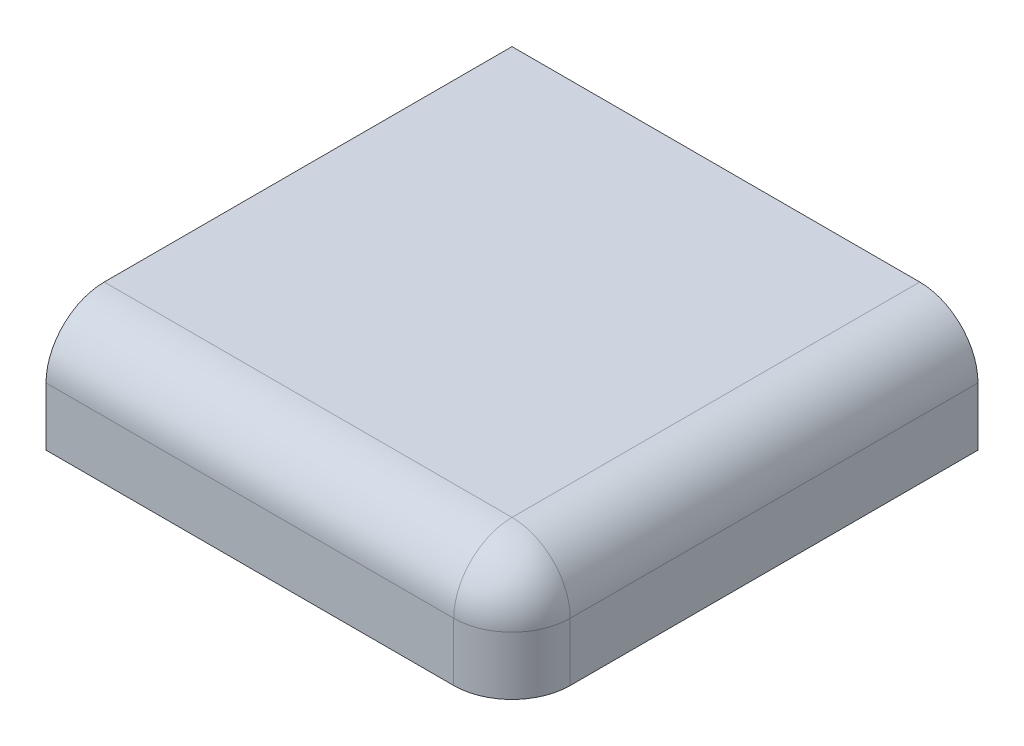
SolidWorks part; units mm, degrees
ref_plane "Front Plane" through (0, 0, 0) normal (0, 0, 1) x (1, 0, 0)
ref_plane "Top Plane" through (0, 0, 0) normal (0, 1, 0) x (1, 0, 0)
ref_plane "Right Plane" through (0, 0, 0) normal (1, 0, 0) x (0, 0, -1)
sketch "Эскиз1" plane through (0, 0, 0) normal (0, 1, 0) x (1, 0, 0)
  line L0 (-20, -20) -> (20, -20)
  line L1 (-20, -20) -> (-20, 20)
  line L2 (20, -20) -> (20, 20)
  line L3 (-20, 20) -> (20, 20)
  line L4 (-20, -20) -> (20, 20) construction
  line L5 (20, -20) -> (-20, 20) construction
  point P1 (0, 0)
  dimension "D1" = 40
  dimension "D2" = 40
extrude "Бобышка-Вытянуть1" add sketch "Эскиз1" against normal blind 10
sketch "Эскиз7" plane through (-20, 0, 0) normal (-1, 0, 0) x (0, 0, 1)
  line L1 (-28.759, -5) -> (30.1285, -5) construction
  line L2 (-20, 0) -> (20, 0) construction
  line L3 (-20, -10) -> (20, -10) construction
  line L4 (0, 5.2438) -> (0, -20.548) construction
  line L5 (0, -2.2258) -> (-1.2875, -2.9692)
  line L6 (0, -2.2258) -> (1.2875, -2.9692)
  circle A0 centre (0, -5.1992) radius 2.575
  point P15 (0, -7.7742)
  dimension "D2" = 5.15
  dimension "D3" = 2.2258
  dimension "D1" = 60
extrude "Вырез-Вытянуть2" cut sketch "Эскиз7" against normal blind 3.15 contours A0 | A0 L6 L5
pattern_circular "Круговой массив1" count 2 over 90 about axis through (0, -10, 0) along (0, -1, 0) of "Вырез-Вытянуть2"
fillet "Скругление2" radius 5 3 edges at (0, 0, 20) (20, 0, 0) (20, -5, 20)
